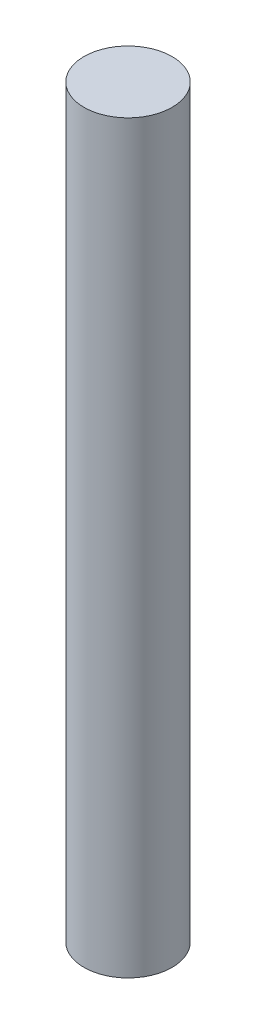
SolidWorks part; units mm, degrees
material "Acrylic (Medium-high impact)"
ref_plane "Front Plane" through (0, 0, 0) normal (0, 0, 1) x (1, 0, 0)
ref_plane "Top Plane" through (0, 0, 0) normal (0, 1, 0) x (1, 0, 0)
ref_plane "Right Plane" through (0, 0, 0) normal (1, 0, 0) x (0, 0, -1)
sketch "Sketch1" plane through (0, 0, 0) normal (0, 1, 0) x (1, 0, 0)
  circle A0 centre (0, 0) radius 3.175
  dimension "D1" = 6.35
extrude "Boss-Extrude1" add sketch "Sketch1" along normal blind 53.7
